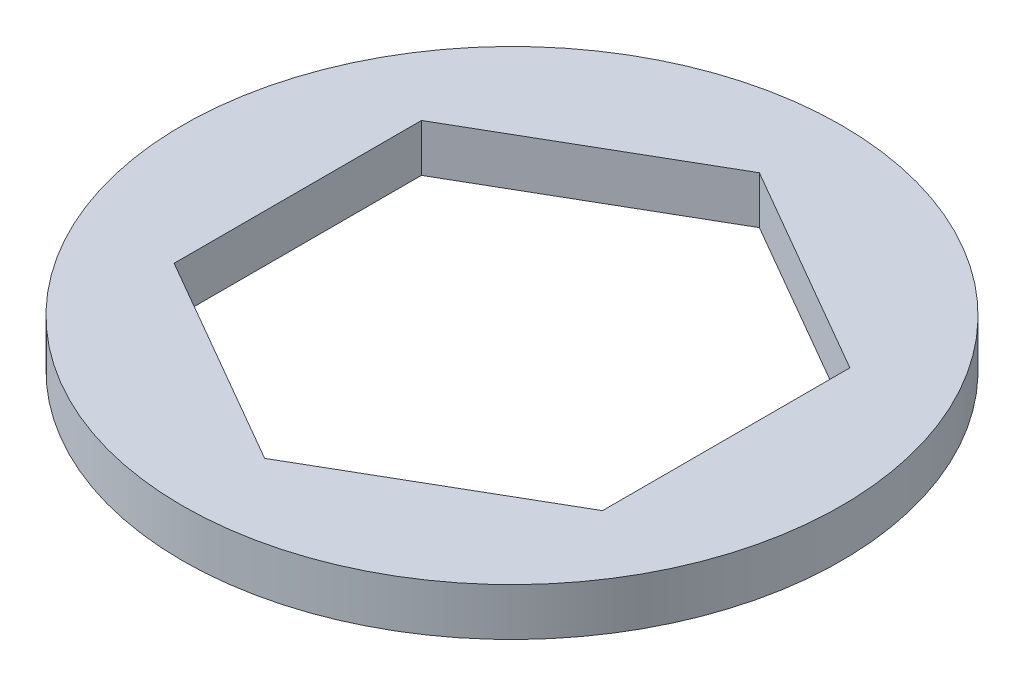
SolidWorks part; units mm, degrees
material "PET"
ref_plane "Front Plane" through (0, 0, 0) normal (0, 0, 1) x (1, 0, 0)
ref_plane "Top Plane" through (0, 0, 0) normal (0, 1, 0) x (1, 0, 0)
ref_plane "Right Plane" through (0, 0, 0) normal (1, 0, 0) x (0, 0, -1)
sketch "Sketch1" plane through (0, 0, 0) normal (0, 1, 0) x (1, 0, 0)
  line L1 (0, 4.1281) -> (-3.575, 2.064)
  line L2 (-3.575, 2.064) -> (-3.575, -2.064)
  line L3 (-3.575, -2.064) -> (0, -4.1281)
  line L4 (0, -4.1281) -> (3.575, -2.064)
  line L5 (3.575, -2.064) -> (3.575, 2.064)
  line L6 (3.575, 2.064) -> (0, 4.1281)
  circle A0 centre (0, 0) radius 3.575 construction
  circle A1 centre (0, 0) radius 5.5
  dimension "D1" = 7.15
  dimension "D2" = 11
extrude "Boss-Extrude1" add sketch "Sketch1" along normal blind 0.7937
